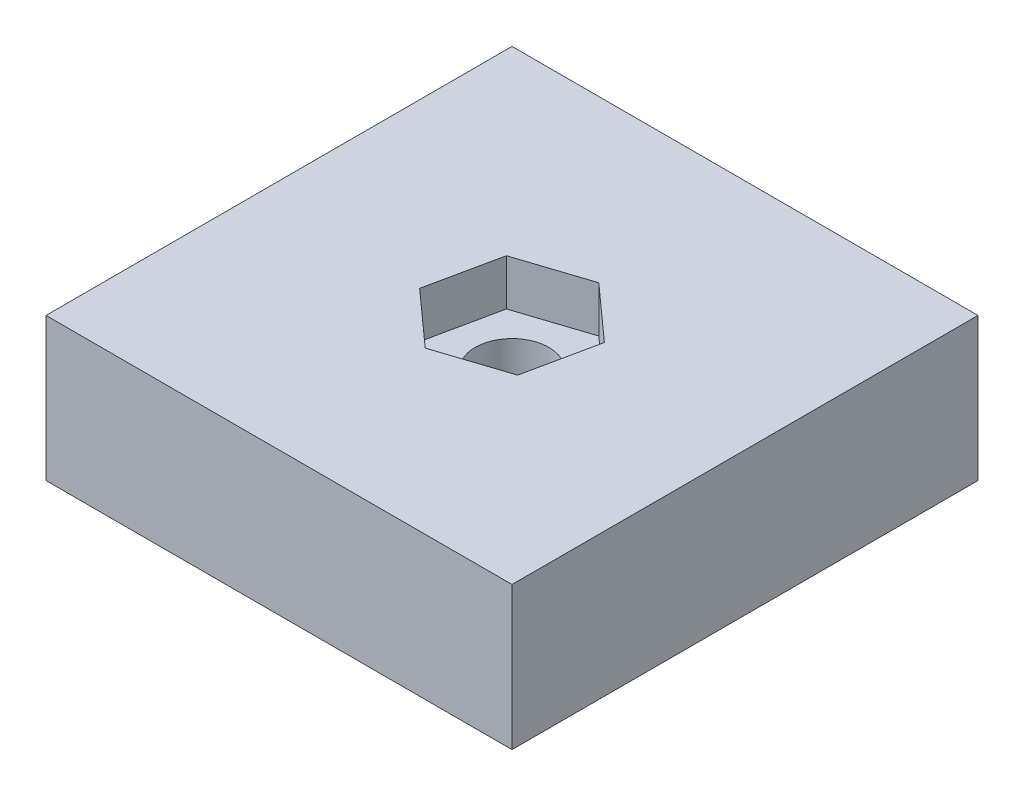
SolidWorks part; units mm, degrees
ref_plane "Front Plane" through (0, 0, 0) normal (0, 0, 1) x (1, 0, 0)
ref_plane "Top Plane" through (0, 0, 0) normal (0, 1, 0) x (1, 0, 0)
ref_plane "Right Plane" through (0, 0, 0) normal (1, 0, 0) x (0, 0, -1)
ref_plane "Plane1" through (0, 6.2, 0) normal (0, 1, 0) x (1, 0, 0)
sketch "Sketch1" plane through (0, 6.2, 0) normal (0, 1, 0) x (1, 0, 0)
  line L0 (20.2, -23) -> (20.2, -2.8)
  line L1 (20.2, -2.8) -> (0, -2.8)
  line L2 (0, -2.8) -> (0, -23)
  line L3 (0, -23) -> (20.2, -23)
extrude "Boss-Extrude1" add sketch "Sketch1" against normal blind 6.2
hole_wizard "Ø3.2 (3.2) Diameter Hole1" positions "Sketch3" profile "Sketch2" hole size "Ø3.2" standard "ANSI Metric"
sketch "Sketch3" plane through (0, 6.2, 0) normal (0, 1, 0) x (1, 0, 0)
  point P0 (10.1, -12.9)
sketch "Sketch2" plane through (10.1, 6.2, 12.9) normal (1, 0, 0) x (0, 0, 1)
  line L0 (0, 0) -> (0, 6.2)
  line L1 (0, 6.2) -> (1.6, 6.2)
  line L2 (1.6, 6.2) -> (1.6, 0)
  line L5 (1.6, 0) -> (0, 0)
  line L11 (0, -6.35) -> (0, 107.95) construction
  dimension "Thru Hole Dia." = 3.2
  dimension "Thru Hole Depth" = 6.2
sketch "Sketch4" plane through (0, 6.2, 0) normal (0, 1, 0) x (1, 0, 0)
  line L7 (10.7551, -9.7929) -> (13.1184, -11.9138)
  line L8 (13.1184, -11.9138) -> (12.4633, -15.0209)
  line L9 (12.4633, -15.0209) -> (9.4449, -16.0071)
  line L10 (9.4449, -16.0071) -> (7.0816, -13.8862)
  line L11 (7.0816, -13.8862) -> (7.7367, -10.7791)
  line L12 (7.7367, -10.7791) -> (10.7551, -9.7929)
  line L13 (20.2, -23) -> (20.2, -2.8) construction
  line L14 (0, -23) -> (20.2, -23) construction
  circle A0 centre (10.1, -12.9) radius 3.1754
  circle A1 centre (10.1, -12.9) radius 1.6 construction
  point P20 (11.9367, -10.8533)
  circle M7 centre (10.1, -12.9) radius 1.6
  dimension "D1" = 120
  dimension "D2" = 5.5
  dimension "D3" = 3.1071
extrude "Cut-Extrude1" cut sketch "Sketch4" against normal blind 2 contours L12 L11 L10 L9 L8 L7 M7
